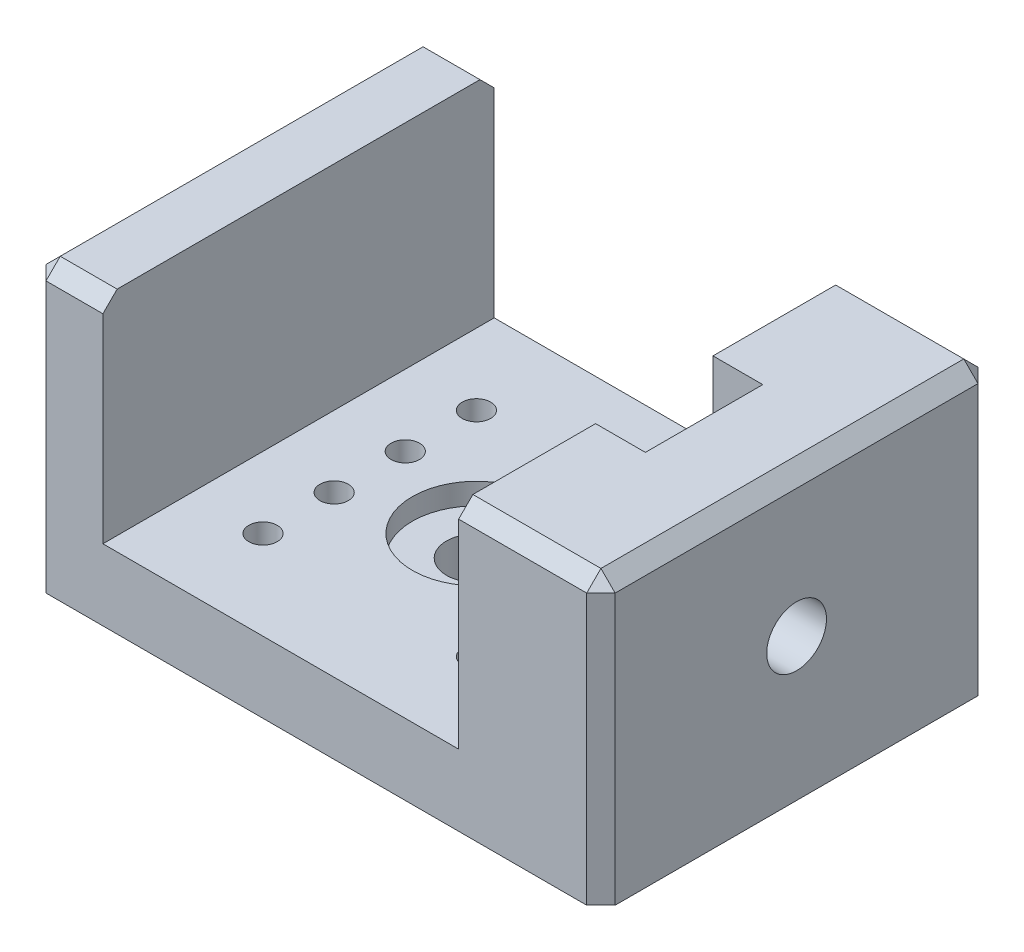
SolidWorks part; units mm, degrees
ref_plane "Front Plane" through (0, 0, 0) normal (0, 0, 1) x (1, 0, 0)
ref_plane "Top Plane" through (0, 0, 0) normal (0, 1, 0) x (1, 0, 0)
ref_plane "Right Plane" through (0, 0, 0) normal (1, 0, 0) x (0, 0, -1)
sketch "Sketch1" plane through (0, 0, 0) normal (0, 0, 1) x (1, 0, 0)
  line L0 (0, 0) -> (35, 0)
  line L1 (35, 0) -> (35, 40)
  line L2 (0, 10) -> (25, 10)
  line L3 (25, 10) -> (25, 40)
  line L4 (25, 40) -> (35, 40)
  line L5 (0, 0) -> (0, 10) construction
  line L6 (-25, 40) -> (-35, 40)
  line L7 (-25, 10) -> (-25, 40)
  line L8 (0, 10) -> (-25, 10)
  line L9 (-35, 0) -> (-35, 40)
  line L10 (0, 0) -> (-35, 0)
  dimension "D1" = 10
  dimension "D2" = 40
  dimension "D3" = 50
extrude "Boss-Extrude1" add sketch "Sketch1" along normal blind 55
sketch "Sketch2" plane through (0, 10, 0) normal (0, 1, 0) x (1, 0, 0)
  line L0 (-25, -55) -> (-25, 0) construction
  line L1 (-15, -12.5) -> (15, -12.5) construction
  line L2 (-15, -12.5) -> (-15, -42.5) construction
  line L3 (-15, -42.5) -> (15, -42.5) construction
  line L4 (15, -12.5) -> (15, -42.5) construction
  line L5 (-15, -12.5) -> (15, -42.5) construction
  line L6 (-15, -42.5) -> (15, -12.5) construction
  line L8 (-15, -22.5) -> (15, -22.5) construction
  line L9 (-15, -22.5) -> (-15, -32.5) construction
  line L10 (-15, -32.5) -> (15, -32.5) construction
  line L11 (15, -22.5) -> (15, -32.5) construction
  line L12 (-15, -22.5) -> (15, -32.5) construction
  line L13 (-15, -32.5) -> (15, -22.5) construction
  circle A0 centre (-15, -12.5) radius 2
  circle A1 centre (-15, -22.5) radius 2
  circle A2 centre (15, -12.5) radius 2
  circle A3 centre (15, -22.5) radius 2
  circle A4 centre (15, -32.5) radius 2
  circle A5 centre (-15, -32.5) radius 2
  circle A6 centre (-15, -42.5) radius 2
  circle A7 centre (15, -42.5) radius 2
  point P0 (0, -27.5)
  point P9 (-25, -27.5)
  point P10 (0, -27.5)
  dimension "D3" = 4
  dimension "D1" = 30
  dimension "D2" = 10
extrude "Cut-Extrude1" cut sketch "Sketch2" against normal through all
sketch "Sketch3" plane through (0, 0, 0) normal (0, -1, 0) x (1, 0, 0)
  line L49 (-10.9585, 12.5) -> (-12.9793, 16)
  line L50 (-12.9793, 16) -> (-17.0207, 16)
  line L51 (-17.0207, 16) -> (-19.0415, 12.5)
  line L52 (-19.0415, 12.5) -> (-17.0207, 9)
  line L53 (-17.0207, 9) -> (-12.9793, 9)
  line L54 (-12.9793, 9) -> (-10.9585, 12.5)
  line L55 (-10.9585, 22.5) -> (-12.9793, 26)
  line L56 (-12.9793, 26) -> (-17.0207, 26)
  line L57 (-17.0207, 26) -> (-19.0415, 22.5)
  line L58 (-19.0415, 22.5) -> (-17.0207, 19)
  line L59 (-17.0207, 19) -> (-12.9793, 19)
  line L60 (-12.9793, 19) -> (-10.9585, 22.5)
  line L61 (-10.9585, 32.5) -> (-12.9793, 36)
  line L62 (-12.9793, 36) -> (-17.0207, 36)
  line L63 (-17.0207, 36) -> (-19.0415, 32.5)
  line L64 (-19.0415, 32.5) -> (-17.0207, 29)
  line L65 (-17.0207, 29) -> (-12.9793, 29)
  line L66 (-12.9793, 29) -> (-10.9585, 32.5)
  line L67 (-10.9585, 42.5) -> (-12.9793, 46)
  line L68 (-12.9793, 46) -> (-17.0207, 46)
  line L69 (-17.0207, 46) -> (-19.0415, 42.5)
  line L70 (-19.0415, 42.5) -> (-17.0207, 39)
  line L71 (-17.0207, 39) -> (-12.9793, 39)
  line L72 (-12.9793, 39) -> (-10.9585, 42.5)
  line L73 (19.0415, 42.5) -> (17.0207, 46)
  line L74 (17.0207, 46) -> (12.9793, 46)
  line L75 (12.9793, 46) -> (10.9585, 42.5)
  line L76 (10.9585, 42.5) -> (12.9793, 39)
  line L77 (12.9793, 39) -> (17.0207, 39)
  line L78 (17.0207, 39) -> (19.0415, 42.5)
  line L79 (19.0415, 32.5) -> (17.0207, 36)
  line L80 (17.0207, 36) -> (12.9793, 36)
  line L81 (12.9793, 36) -> (10.9585, 32.5)
  line L82 (10.9585, 32.5) -> (12.9793, 29)
  line L83 (12.9793, 29) -> (17.0207, 29)
  line L84 (17.0207, 29) -> (19.0415, 32.5)
  line L85 (19.0415, 22.5) -> (17.0207, 26)
  line L86 (17.0207, 26) -> (12.9793, 26)
  line L87 (12.9793, 26) -> (10.9585, 22.5)
  line L88 (10.9585, 22.5) -> (12.9793, 19)
  line L89 (12.9793, 19) -> (17.0207, 19)
  line L90 (17.0207, 19) -> (19.0415, 22.5)
  line L91 (19.0415, 12.5) -> (17.0207, 16)
  line L92 (17.0207, 16) -> (12.9793, 16)
  line L93 (12.9793, 16) -> (10.9585, 12.5)
  line L94 (10.9585, 12.5) -> (12.9793, 9)
  line L95 (12.9793, 9) -> (17.0207, 9)
  line L96 (17.0207, 9) -> (19.0415, 12.5)
  circle A0 centre (-15, 12.5) radius 3.5 construction
  circle A1 centre (-15, 22.5) radius 3.5 construction
  circle A2 centre (-15, 32.5) radius 3.5 construction
  circle A3 centre (-15, 42.5) radius 3.5 construction
  circle A4 centre (15, 42.5) radius 3.5 construction
  circle A5 centre (15, 32.5) radius 3.5 construction
  circle A6 centre (15, 22.5) radius 3.5 construction
  circle A7 centre (15, 12.5) radius 3.5 construction
  point P64 (0, 0)
  dimension "D1" = 7
extrude "Cut-Extrude2" cut sketch "Sketch3" against normal blind 3
sketch "Sketch4" plane through (0, 10, 0) normal (0, 1, 0) x (1, 0, 0)
  line L0 (-25, -55) -> (-25, 0) construction
  circle A0 centre (0, -27.5) radius 4.2
  point P4 (-25, -27.5)
  point P5 (0, 0)
  dimension "D1" = 8.4
extrude "Cut-Extrude3" cut sketch "Sketch4" against normal through all
sketch "Sketch5" plane through (0, 10, 0) normal (0, 1, 0) x (1, 0, 0)
  circle A0 centre (0, -27.5) radius 9
  dimension "D1" = 18
extrude "Cut-Extrude4" cut sketch "Sketch5" against normal blind 3
sketch "Sketch6" plane through (35, 0, 0) normal (1, 0, 0) x (0, 0, -1)
  line L0 (-55, 0) -> (0, 0) construction
  circle A0 centre (-27.5, 20) radius 4.2
  point P4 (-27.5, 0)
  dimension "D1" = 20
  dimension "D2" = 8.4
extrude "Cut-Extrude5" cut sketch "Sketch6" against normal blind 10
sketch "Sketch7" plane through (25, 0, 0) normal (-1, 0, 0) x (0, 0, 1)
  line L0 (55, 40) -> (0, 40) construction
  line L1 (19.25, 40) -> (35.75, 40)
  line L2 (19.25, 40) -> (19.25, 10)
  line L3 (19.25, 10) -> (35.75, 10)
  line L4 (35.75, 40) -> (35.75, 10)
  line L5 (55, 10) -> (0, 10) construction
  point P8 (27.5, 40)
  point P9 (27.5, 40)
  dimension "D1" = 16.5
extrude "Cut-Extrude6" cut sketch "Sketch7" against normal blind 7
sketch "Sketch8" plane through (35, 0, 0) normal (1, 0, 0) x (0, 0, -1)
  line L4 (0, 0) -> (0, 40)
  line L5 (0, 40) -> (-55, 40)
  line L6 (-55, 40) -> (-55, 0)
  line L7 (-55, 0) -> (0, 0)
  line L8 (0, 0) -> (0, 40)
  line L9 (0, 40) -> (-55, 40)
  line L10 (-55, 40) -> (-55, 0)
  line L11 (-55, 0) -> (0, 0)
  circle A0 centre (-27.5, 20) radius 4.2 construction
  circle A1 centre (-27.5, 20) radius 4.2
  dimension "D1" = 0
extrude "Boss-Extrude2" add sketch "Sketch8" along normal blind 10
chamfer "Chamfer1" distance 2 angle 45 10 edges at (45, 20, 0) (35, 40, 0) (45, 40, 27.5) (45, 20, 55) (35, 40, 55) (-35, 20, 0) (-30, 40, 0) (-35, 40, 27.5) (-35, 20, 55) (-30, 40, 55)
